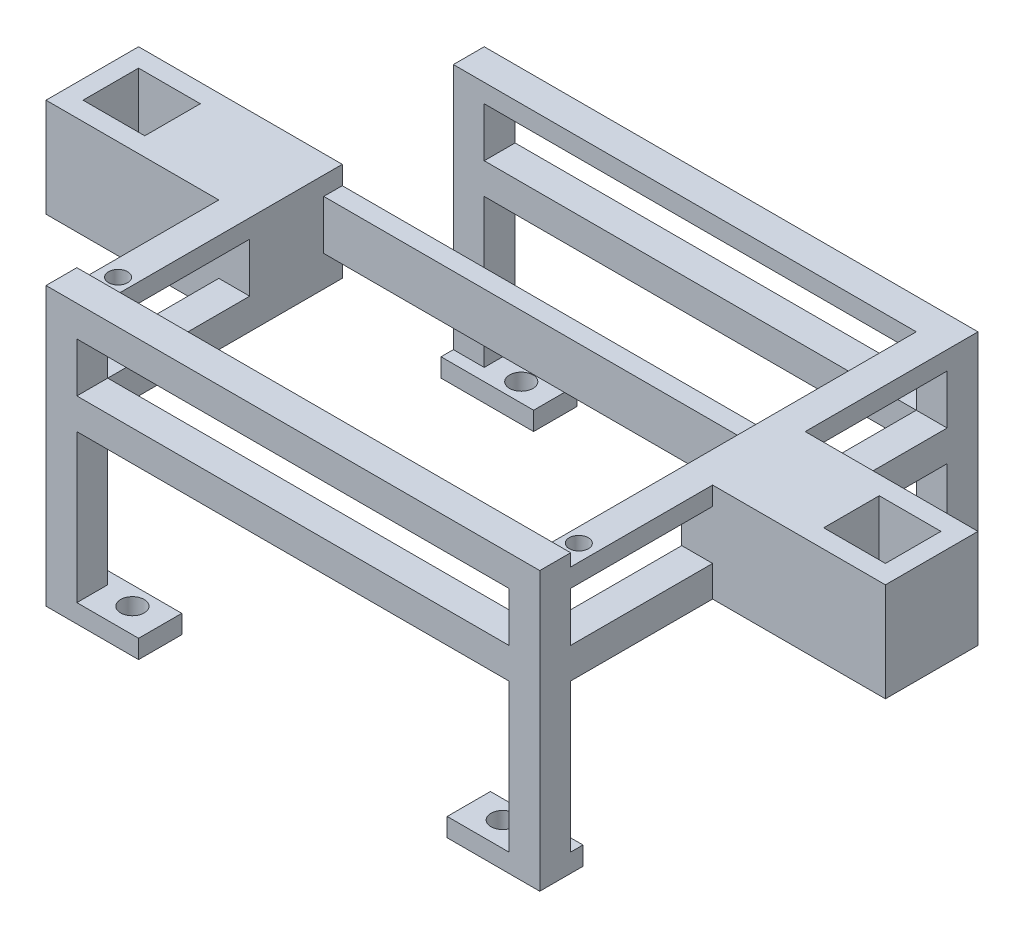
SolidWorks part; units mm, degrees
ref_plane "Front Plane" through (0, 0, 0) normal (0, 0, 1) x (1, 0, 0)
ref_plane "Top Plane" through (0, 0, 0) normal (0, 1, 0) x (1, 0, 0)
ref_plane "Right Plane" through (0, 0, 0) normal (1, 0, 0) x (0, 0, -1)
sketch "Sketch1" plane through (0, 0, 0) normal (0, 1, 0) x (1, 0, 0)
  line L0 (0, 0) -> (41.2763, 0) construction
  line L1 (25, 35.5) -> (40, 35.5)
  line L2 (25, 35.5) -> (25, 28.5)
  line L3 (25, 28.5) -> (40, 28.5)
  line L4 (40, 35.5) -> (40, 28.5)
  line L5 (0, 0) -> (0, 31.5847) construction
  line L6 (40, -35.5) -> (40, -28.5)
  line L7 (25, -28.5) -> (40, -28.5)
  line L8 (25, -35.5) -> (25, -28.5)
  line L9 (25, -35.5) -> (40, -35.5)
  line L10 (-25, -35.5) -> (-40, -35.5)
  line L11 (-25, -35.5) -> (-25, -28.5)
  line L12 (-25, -28.5) -> (-40, -28.5)
  line L13 (-40, -35.5) -> (-40, -28.5)
  line L14 (-40, 35.5) -> (-40, 28.5)
  line L15 (-25, 28.5) -> (-40, 28.5)
  line L16 (-25, 35.5) -> (-25, 28.5)
  line L17 (-25, 35.5) -> (-40, 35.5)
  circle A0 centre (30, 31.5) radius 1.9
  circle A1 centre (30, -31.5) radius 1.9
  circle A2 centre (-30, -31.5) radius 1.9
  circle A3 centre (-30, 31.5) radius 1.9
  dimension "D4" = 3.8
  dimension "D1" = 7
  dimension "D2" = 15
  dimension "D3" = 4
  dimension "D5" = 5
  dimension "D6" = 71
  dimension "D7" = 60
extrude "Boss-Extrude1" add sketch "Sketch1" along normal blind 3
sketch "Sketch2" plane through (0, 3, 0) normal (0, 1, 0) x (1, 0, 0)
  line L0 (0, 0) -> (11.9674, 0) construction
  line L1 (40, 35.5) -> (35, 35.5)
  line L2 (40, 35.5) -> (40, 30.5)
  line L3 (40, 30.5) -> (35, 30.5)
  line L4 (35, 35.5) -> (35, 30.5)
  line L5 (0, 0) -> (0, 11.9158) construction
  line L6 (35, -35.5) -> (35, -30.5)
  line L7 (40, -30.5) -> (35, -30.5)
  line L8 (40, -35.5) -> (40, -30.5)
  line L9 (40, -35.5) -> (35, -35.5)
  line L10 (-40, -35.5) -> (-35, -35.5)
  line L11 (-40, -35.5) -> (-40, -30.5)
  line L12 (-40, -30.5) -> (-35, -30.5)
  line L13 (-35, -35.5) -> (-35, -30.5)
  line L14 (-35, 35.5) -> (-35, 30.5)
  line L15 (-40, 30.5) -> (-35, 30.5)
  line L16 (-40, 35.5) -> (-40, 30.5)
  line L17 (-40, 35.5) -> (-35, 35.5)
  dimension "D1" = 5
  dimension "D2" = 5
extrude "Boss-Extrude2" add sketch "Sketch2" along normal blind 37
sketch "Sketch4" plane through (0, 40, 0) normal (0, 1, 0) x (1, 0, 0)
  line L1 (40, 30.5) -> (35, 30.5)
  line L2 (40, 30.5) -> (40, -30.5)
  line L3 (40, -30.5) -> (35, -30.5)
  line L4 (35, 30.5) -> (35, -30.5)
  line L6 (40, -30.5) -> (35, -30.5) construction
  line L7 (35, 30.5) -> (40, 30.5) construction
  line L8 (0, 0) -> (0, 8.8915) construction
  line L9 (-35, 30.5) -> (-35, -30.5)
  line L10 (-40, -30.5) -> (-35, -30.5)
  line L11 (-40, 30.5) -> (-40, -30.5)
  line L12 (-40, 30.5) -> (-35, 30.5)
  dimension "D1" = 5
extrude "Boss-Extrude3" add sketch "Sketch4" along normal blind 3 separate body
sketch "Sketch5" plane through (0, 40, 0) normal (0, 1, 0) x (1, 0, 0)
  line L1 (40, 35.5) -> (-40, 35.5)
  line L2 (40, 35.5) -> (40, 30.5)
  line L3 (40, 30.5) -> (-40, 30.5)
  line L4 (-40, 35.5) -> (-40, 30.5)
extrude "Boss-Extrude5" add sketch "Sketch5" along normal blind 3
sketch "Sketch6" plane through (0, 40, 0) normal (0, 1, 0) x (1, 0, 0)
  line L1 (40, -35.5) -> (-40, -35.5)
  line L2 (40, -35.5) -> (40, -30.5)
  line L3 (40, -30.5) -> (-40, -30.5)
  line L4 (-40, -35.5) -> (-40, -30.5)
extrude "Boss-Extrude6" add sketch "Sketch6" along normal blind 5
sketch "Sketch7" plane through (0, 43, 0) normal (0, 1, 0) x (1, 0, 0)
  line L0 (0, 0) -> (0, 10.7589) construction
  line L2 (-40, -30.5) -> (-35, -30.5) construction
  circle A0 centre (-37.325, -26.5) radius 1.55
  circle A1 centre (37.325, -26.5) radius 1.55
  point P9 (-37.5, -30.5)
  dimension "D1" = 3.1
  dimension "D2" = 74.65
  dimension "D3" = 4
extrude "Cut-Extrude1" cut sketch "Sketch7" against normal blind 3
sketch "Sketch8" plane through (0, 0, 35.5) normal (0, 0, 1) x (1, 0, 0)
  line L0 (-35, 40) -> (-35, 3) construction
  line L1 (-35, 32) -> (35, 32)
  line L2 (-35, 32) -> (-35, 27)
  line L3 (-35, 27) -> (35, 27)
  line L4 (35, 32) -> (35, 27)
  line L5 (35, 40) -> (35, 3) construction
  line L7 (-25, 3) -> (-35, 3) construction
  line L9 (-35, 40) -> (35, 40) construction
  point P10 (-30, 3)
  dimension "D1" = 13
  dimension "D2" = 5
extrude "Boss-Extrude7" add sketch "Sketch8" against normal blind 5
ref_plane "Plane1" through (0, 0, 0) normal (0, 0, 1) x (1, 0, 0)
ref_plane "Plane2" through (0, 0, 0) normal (1, 0, 0) x (0, 0, -1)
mirror "Mirror1" about plane through (0, 0, 0) normal (0, 0, 1) of "Boss-Extrude7"
sketch "Sketch9" plane through (40, 0, 0) normal (1, 0, 0) x (0, 0, -1)
  line L0 (-30.5, 40) -> (-30.5, 3) construction
  line L1 (-30.5, 32) -> (30.5, 32)
  line L2 (-30.5, 32) -> (-30.5, 27)
  line L3 (-30.5, 27) -> (30.5, 27)
  line L4 (30.5, 32) -> (30.5, 27)
  line L5 (30.5, 40) -> (30.5, 3) construction
  line L6 (-30.5, 40) -> (30.5, 40) construction
  dimension "D1" = 5
  dimension "D2" = 13
extrude "Boss-Extrude8" add sketch "Sketch9" against normal blind 5
mirror "Mirror2" about plane through (0, 0, 0) normal (1, 0, 0) of "Boss-Extrude8"
sketch "Sketch13" plane through (0, 43, 0) normal (0, 1, 0) x (1, 0, 0)
  line L0 (35, 7.5) -> (35, -7.5)
  line L1 (35, 7.5) -> (68, 7.5)
  line L2 (35, 30.5) -> (35, -30.5) construction
  line L3 (35, -7.5) -> (68, -7.5)
  line L4 (68, 7.5) -> (68, -7.5)
  line L5 (-24.75, 0) -> (24.75, 0) construction
  line L7 (0, -24.75) -> (0, 24.75) construction
  line L8 (55, 4.5) -> (65, 4.5)
  line L9 (55, 4.5) -> (55, -4.5)
  line L11 (55, -4.5) -> (65, -4.5)
  line L12 (65, 4.5) -> (65, -4.5)
  dimension "D1" = 15
  dimension "D2" = 4.5
  dimension "D3" = 7.5
  dimension "55" = 55
  dimension "D5" = 9
  dimension "D6" = 10
  dimension "D7" = 3
extrude "Boss-Extrude10" add sketch "Sketch13" against normal blind 16
mirror "Mirror3" about plane through (0, 0, 0) normal (1, 0, 0) of "Boss-Extrude10"
sketch "Sketch14" plane through (-35, 0, 0) normal (1, 0, 0) x (0, 0, -1)
  line L0 (30.5, 32) -> (7.5, 32) construction
  line L1 (7.5, 40) -> (4.5, 40)
  line L2 (7.5, 40) -> (7.5, 32)
  line L3 (7.5, 32) -> (4.5, 32)
  line L4 (4.5, 40) -> (4.5, 32)
  dimension "D1" = 3
extrude "Boss-Extrude11" add sketch "Sketch14" along normal blind 70
sketch "Sketch15" plane through (0, 43, 0) normal (0, 1, 0) x (1, 0, 0)
  line L1 (-35, 30.5) -> (-40, 30.5)
  line L2 (-35, 30.5) -> (-35, 7.5)
  line L3 (-35, 7.5) -> (-40, 7.5)
  line L4 (-40, 30.5) -> (-40, 7.5)
extrude "Cut-Extrude4" cut sketch "Sketch15" against normal blind 16
